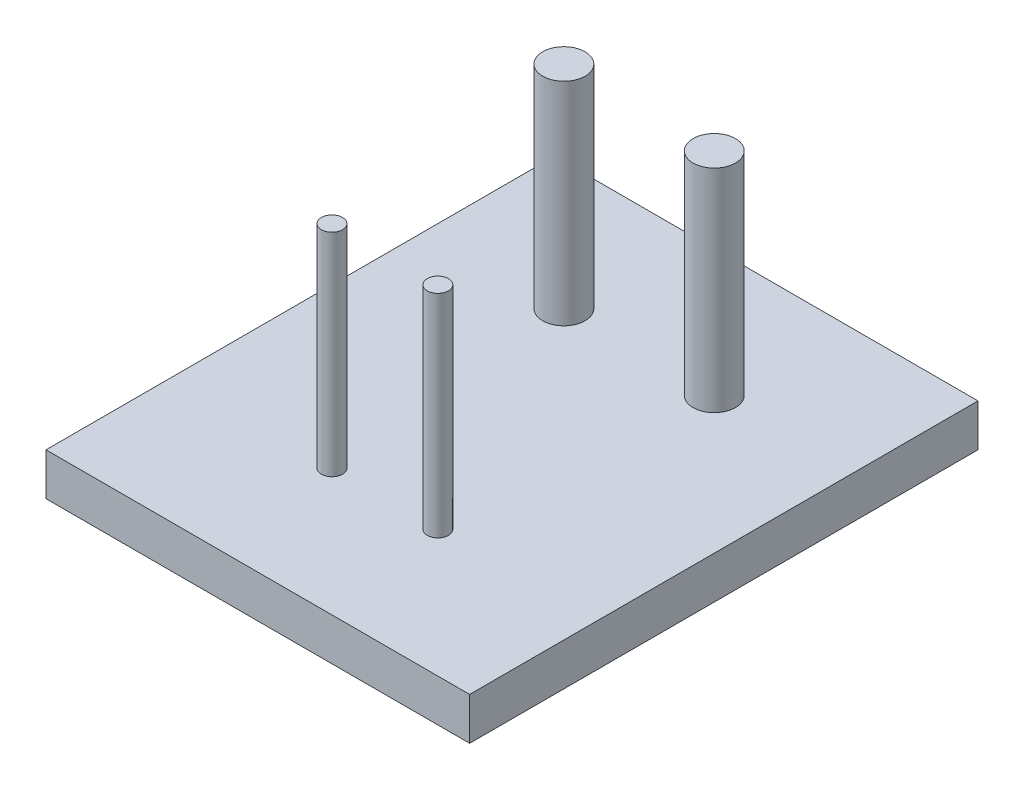
SolidWorks part; units mm, degrees
ref_plane "Front Plane" through (0, 0, 0) normal (0, 0, 1) x (1, 0, 0)
ref_plane "Top Plane" through (0, 0, 0) normal (0, 1, 0) x (1, 0, 0)
ref_plane "Right Plane" through (0, 0, 0) normal (1, 0, 0) x (0, 0, -1)
sketch "Sketch1" plane through (0, 0, 0) normal (0, 1, 0) x (1, 0, 0)
  line L1 (50, -60) -> (-50, -60)
  line L2 (50, -60) -> (50, 60)
  line L3 (50, 60) -> (-50, 60)
  line L4 (-50, -60) -> (-50, 60)
  line L5 (50, -60) -> (-50, 60) construction
  line L6 (50, 60) -> (-50, -60) construction
  point P0 (0, 0)
  dimension "D1" = 100
  dimension "D2" = 120
extrude "Boss-Extrude1" add sketch "Sketch1" along normal mid plane 10
sketch "Sketch2" plane through (0, 5, 0) normal (0, 1, 0) x (1, 0, 0)
  line L0 (0, 0) -> (0, 60) construction
  line L1 (50, 60) -> (-50, 60) construction
  line L2 (-50, -60) -> (50, -60) construction
  circle A0 centre (-17.75, 30) radius 5
  circle A1 centre (17.75, 30) radius 5
  circle A2 centre (-12.5, -30) radius 2.5
  circle A3 centre (12.5, -30) radius 2.5
  point P9 (12.5, -30)
  point P10 (-12.5, -30)
  dimension "D1" = 10
  dimension "D6" = 5
  dimension "D2" = 35.5
  dimension "D3" = 30
  dimension "D4" = 25
  dimension "D5" = 30
extrude "Boss-Extrude2" add sketch "Sketch2" along normal blind 50
